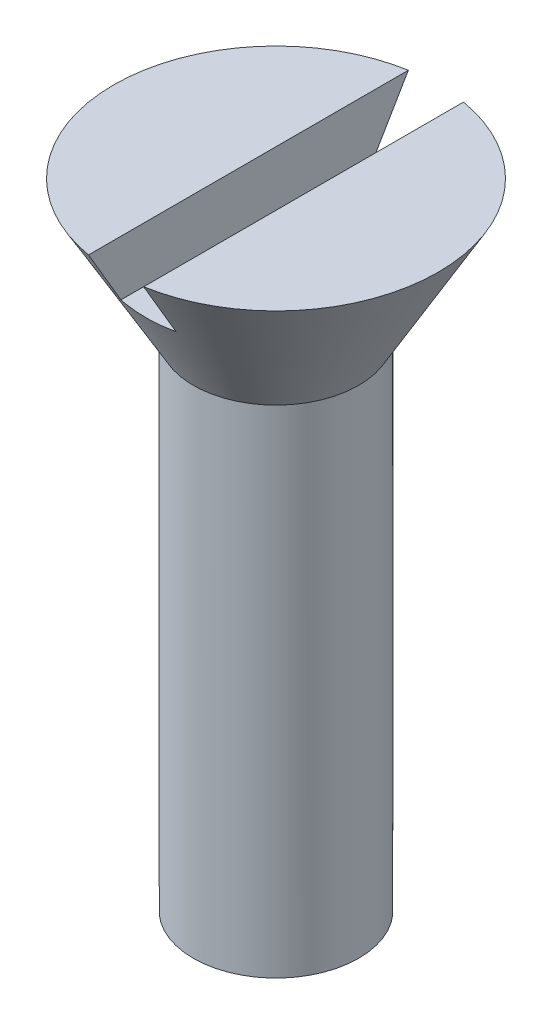
SolidWorks part; units mm, degrees
ref_plane "Front Plane" through (0, 0, 0) normal (0, 0, 1) x (1, 0, 0)
ref_plane "Top Plane" through (0, 0, 0) normal (0, 1, 0) x (1, 0, 0)
ref_plane "Right Plane" through (0, 0, 0) normal (1, 0, 0) x (0, 0, -1)
sketch "Sketch1" plane through (0, 0, 0) normal (0, 0, 1) x (1, 0, 0)
  line L1 (-3, 0) -> (-3, 18)
  line L2 (0, 23) -> (-5.8868, 23)
  line L3 (0, 0) -> (0, 23)
  line L4 (-5.8868, 23) -> (-3, 18)
  line L5 (-3, 0) -> (0, -1.7321)
  line L6 (0, -1.7321) -> (0, 0)
  dimension "D1" = 18
  dimension "D2" = 3
  dimension "D3" = 60
  dimension "D4" = 23
  dimension "D5" = 60
revolve "Revolve1" add sketch "Sketch1" angle 360 about L3
cosmetic thread "Cosmetic Thread3" parameters "D1"=5, "D2"=5.4
sketch "Sketch2" plane through (0, 0, 0) normal (0, 0, 1) x (1, 0, 0)
  line L0 (5.8868, 23) -> (-5.8868, 23) construction
  line L1 (-1, 23) -> (1, 23)
  line L2 (-1, 23) -> (-1, 21)
  line L3 (-1, 21) -> (1, 21)
  line L4 (1, 23) -> (1, 21)
  line L5 (-3, 18) -> (-3, 0) construction
  dimension "D1" = 2
  dimension "D2" = 2
  dimension "D3" = 2
extrude "Extrude1" cut sketch "Sketch2" against normal up to next and the other way up to next
